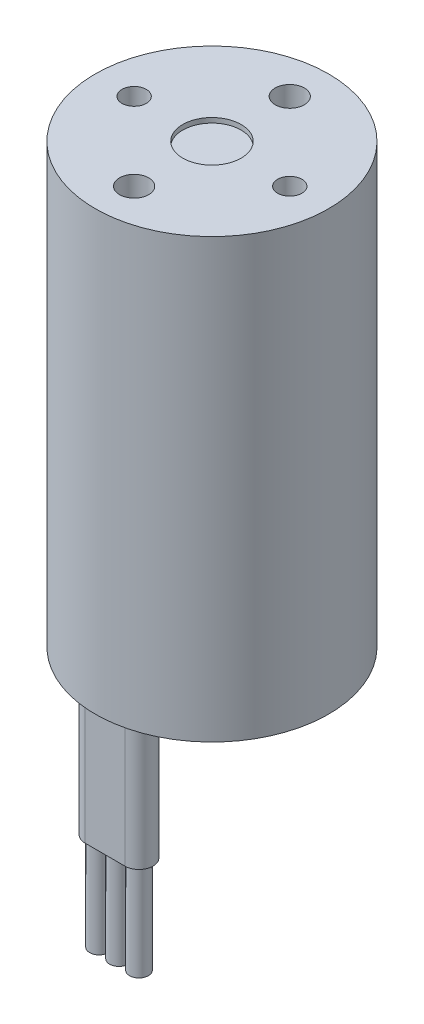
SolidWorks part; units mm, degrees
ref_plane "Front Plane" through (0, 0, 0) normal (0, 0, 1) x (1, 0, 0)
ref_plane "Top Plane" through (0, 0, 0) normal (0, 1, 0) x (1, 0, 0)
ref_plane "Right Plane" through (0, 0, 0) normal (1, 0, 0) x (0, 0, -1)
sketch "Sketch1" plane through (0, 0, 0) normal (0, 1, 0) x (1, 0, 0)
  circle A0 centre (0, 0) radius 12
  dimension "D1" = 24
extrude "MotorCase" add sketch "Sketch1" along normal blind 45
sketch "Screwplacement" plane through (0, 45, 0) normal (0, 1, 0) x (1, 0, 0)
  point P0 (-8, 0)
  point P5 (0, 8)
  point P6 (8, 0)
  point P7 (0, -8)
  point P8 (0, 0)
  dimension "D1" = 8
hole_wizard "M2.5" positions "Sketch8" profile "Sketch7" hole size "Ø2.5" standard "ANSI Metric"
sketch "Sketch8" plane through (0, 45, 0) normal (0, 1, 0) x (1, 0, 0)
  point P0 (8, 0)
  point P3 (-8, 0)
sketch "Sketch7" plane through (8, 45, 0) normal (1, 0, 0) x (0, 0, 1)
  line L0 (0, 0) -> (0, 4.7511)
  line L1 (0, 4.7511) -> (1.25, 4)
  line L2 (1.25, 4) -> (1.25, 0)
  line L5 (1.25, 0) -> (0, 0)
  line L10 (0, 4.7511) -> (-1.25, 4) construction
  line L11 (0, -6.35) -> (0, 107.95) construction
  dimension "Hole Dia." = 2.5
  dimension "Hole Depth" = 4
  dimension "Drill Angle" = 118
hole_wizard "M3" positions "Sketch10" profile "Sketch9" hole size "Ø3.0" standard "ANSI Metric"
sketch "Sketch10" plane through (0, 45, 0) normal (0, 1, 0) x (1, 0, 0)
  point P0 (0, 8)
  point P3 (0, -8)
sketch "Sketch9" plane through (0, 45, -8) normal (1, 0, 0) x (0, 0, 1)
  line L0 (0, 0) -> (0, 4.9013)
  line L1 (0, 4.9013) -> (1.5, 4)
  line L2 (1.5, 4) -> (1.5, 0)
  line L5 (1.5, 0) -> (0, 0)
  line L10 (0, 4.9013) -> (-1.5, 4) construction
  line L11 (0, -6.35) -> (0, 107.95) construction
  dimension "Hole Dia." = 3
  dimension "Hole Depth" = 4
  dimension "Drill Angle" = 118
sketch "Sketch14" plane through (0, 0, 0) normal (0, -1, 0) x (1, 0, 0)
  line L0 (-2.0536, 9.5536) -> (2.0536, 9.5536) construction
  line L1 (-2.0536, 11) -> (2.0536, 11)
  line L2 (-2.0536, 8.1072) -> (2.0536, 8.1072)
  arc A0 (-2.0536, 11) -> (-2.0536, 8.1072) centre (-2.0536, 9.5536) ccw
  arc A1 (2.0536, 8.1072) -> (2.0536, 11) centre (2.0536, 9.5536) ccw
  point P2 (0, 9.5536)
  point P7 (-3.5, 9.5536)
  point P8 (3.5, 9.5536)
  dimension "D1" = 7
  dimension "D2" = 11
extrude "Boss-Extrude1" add sketch "Sketch14" along normal blind 13
sketch "Sketch15" plane through (0, -13, 0) normal (0, -1, 0) x (1, 0, 0)
  circle A0 centre (-2.0536, 9.5536) radius 0.9666
  circle A1 centre (0, 9.5536) radius 0.9666
  circle A2 centre (2.0536, 9.5536) radius 0.9666
  arc A3 (2.0536, 8.1072) -> (2.0536, 11) centre (2.0536, 9.5536) ccw construction
  arc A4 (-2.0536, 11) -> (-2.0536, 8.1072) centre (-2.0536, 9.5536) ccw construction
extrude "Boss-Extrude2" add sketch "Sketch15" along normal blind 10
sketch "Sketch16" plane through (0, 0, 0) normal (0, -1, 0) x (1, 0, 0)
  circle A0 centre (0, 0) radius 3
  dimension "D1" = 6
extrude "Cut-Extrude2" cut sketch "Sketch16" against normal blind 0.5
sketch "Sketch17" plane through (0, 45, 0) normal (0, 1, 0) x (1, 0, 0)
  circle A0 centre (0, 0) radius 3
  dimension "D1" = 6
extrude "Cut-Extrude3" cut sketch "Sketch17" against normal blind 0.5
